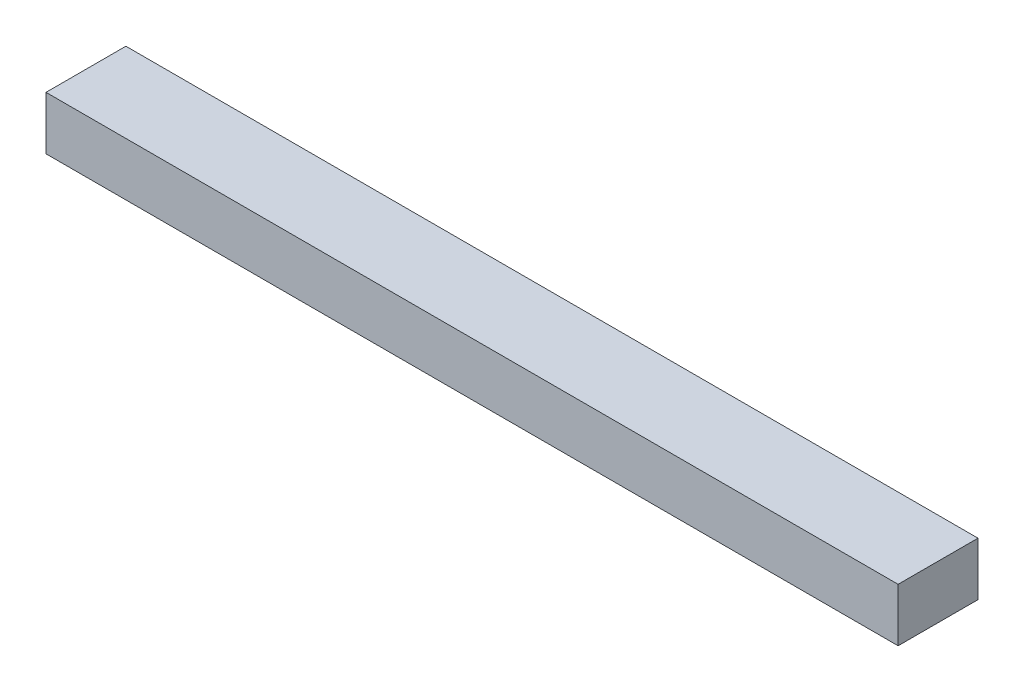
SolidWorks part; units mm, degrees
ref_plane "Front Plane" through (0, 0, 0) normal (0, 0, 1) x (1, 0, 0)
ref_plane "Top Plane" through (0, 0, 0) normal (0, 1, 0) x (1, 0, 0)
ref_plane "Right Plane" through (0, 0, 0) normal (1, 0, 0) x (0, 0, -1)
sketch "Sketch1" plane through (0, 0, 0) normal (0, 1, 0) x (1, 0, 0)
  line L1 (-160, -15) -> (160, -15)
  line L2 (-160, -15) -> (-160, 15)
  line L3 (-160, 15) -> (160, 15)
  line L4 (160, -15) -> (160, 15)
  line L5 (-160, -15) -> (160, 15) construction
  line L6 (-160, 15) -> (160, -15) construction
  point P0 (0, 0)
  dimension "D1" = 320
  dimension "D2" = 30
extrude "Boss-Extrude1" add sketch "Sketch1" along normal blind 20
